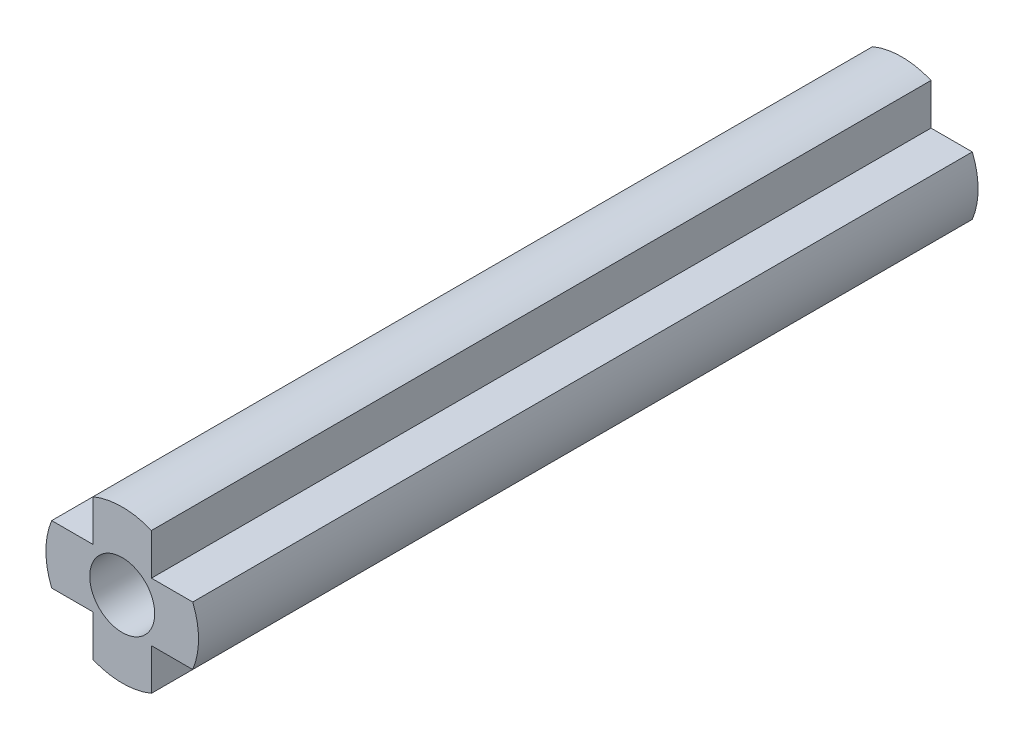
SolidWorks part; units mm, degrees
ref_plane "Front Plane" through (0, 0, 0) normal (0, 0, 1) x (1, 0, 0)
ref_plane "Top Plane" through (0, 0, 0) normal (0, 1, 0) x (1, 0, 0)
ref_plane "Right Plane" through (0, 0, 0) normal (1, 0, 0) x (0, 0, -1)
sketch "Sketch1" plane through (0, 0, 0) normal (0, 0, 1) x (1, 0, 0)
  line L0 (-0.9, 2.1708) -> (-0.9, 0.9)
  line L1 (0.9, 2.1708) -> (0.9, 0.9)
  line L2 (-2.1708, 0.9) -> (-0.9, 0.9)
  line L3 (-2.1708, -0.9) -> (-0.9, -0.9)
  line L4 (-0.9, -0.9) -> (-0.9, -2.1708)
  line L5 (0.9, 0.9) -> (2.1708, 0.9)
  line L6 (0.9, -0.9) -> (0.9, -2.1708)
  line L7 (0.9, -0.9) -> (2.1708, -0.9)
  arc A0 (-0.9, -2.1708) -> (0.9, -2.1708) centre (0, 0) ccw
  arc A1 (2.1708, -0.9) -> (2.1708, 0.9) centre (0, 0) ccw
  arc A2 (0.9, 2.1708) -> (-0.9, 2.1708) centre (0, 0) ccw
  arc A3 (-2.1708, 0.9) -> (-2.1708, -0.9) centre (0, 0) ccw
  dimension "D1" = 4.7
  dimension "D2" = 0.9
  dimension "D3" = 1.8
  dimension "D4" = 0.9
  dimension "D5" = 1.8
extrude "Boss-Extrude1" add sketch "Sketch1" along normal blind 24
sketch "Sketch2" plane through (0, 0, 24) normal (0, 0, 1) x (1, 0, 0)
  circle A0 centre (0, 0) radius 1
  dimension "D1" = 2
extrude "Cut-Extrude1" cut sketch "Sketch2" against normal blind 13
